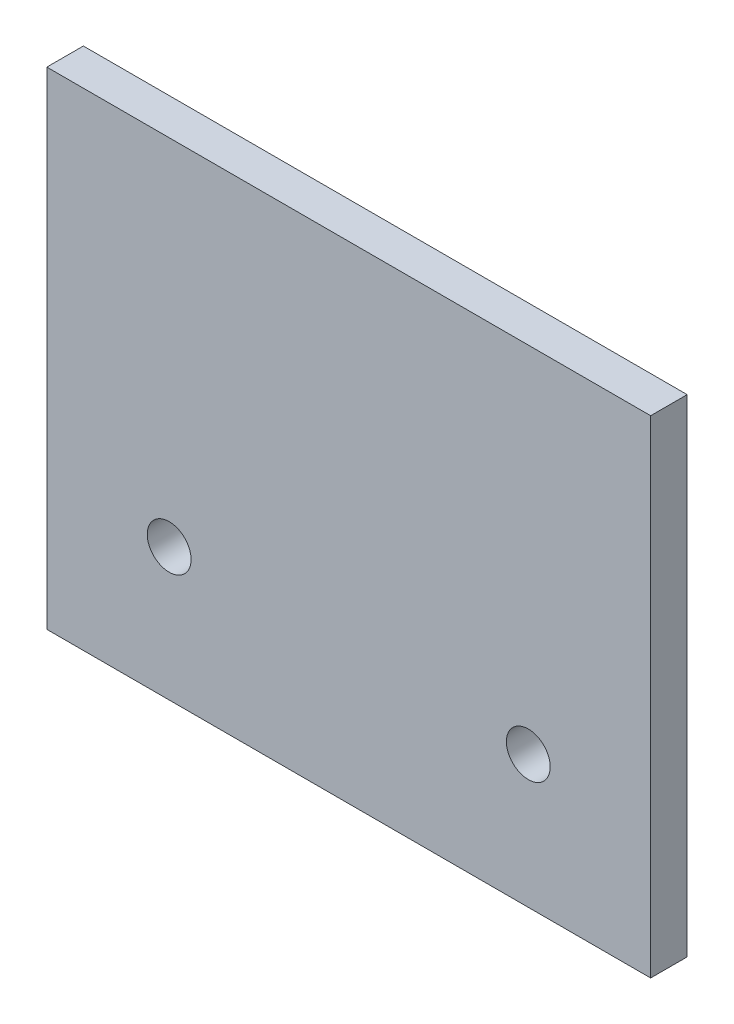
SolidWorks part; units mm, degrees
ref_plane "Front Plane" through (0, 0, 0) normal (0, 0, 1) x (1, 0, 0)
ref_plane "Top Plane" through (0, 0, 0) normal (0, 1, 0) x (1, 0, 0)
ref_plane "Right Plane" through (0, 0, 0) normal (1, 0, 0) x (0, 0, -1)
sketch "Sketch1" plane through (0, 0, 0) normal (0, 0, 1) x (1, 0, 0)
  line L1 (-67.8128, 8.2114) -> (-18.2128, 8.2114)
  line L2 (-67.8128, 8.2114) -> (-67.8128, 48.2114)
  line L3 (-67.8128, 48.2114) -> (-18.2128, 48.2114)
  line L4 (-18.2128, 8.2114) -> (-18.2128, 48.2114)
  circle A4 centre (-28.2628, 19.1013) radius 1.8 construction
  circle A5 centre (-57.7628, 19.1013) radius 1.8 construction
  circle A6 centre (-28.2628, 19.1013) radius 1.8
  circle A7 centre (-57.7628, 19.1013) radius 1.8
  point P4 (-67.8128, 51.2114)
  point P7 (-67.8128, 48.2114)
  point P9 (0, 0)
  dimension "D1" = 49.6
  dimension "D2" = 40
extrude "Boss-Extrude1" add sketch "Sketch1" along normal blind 3
